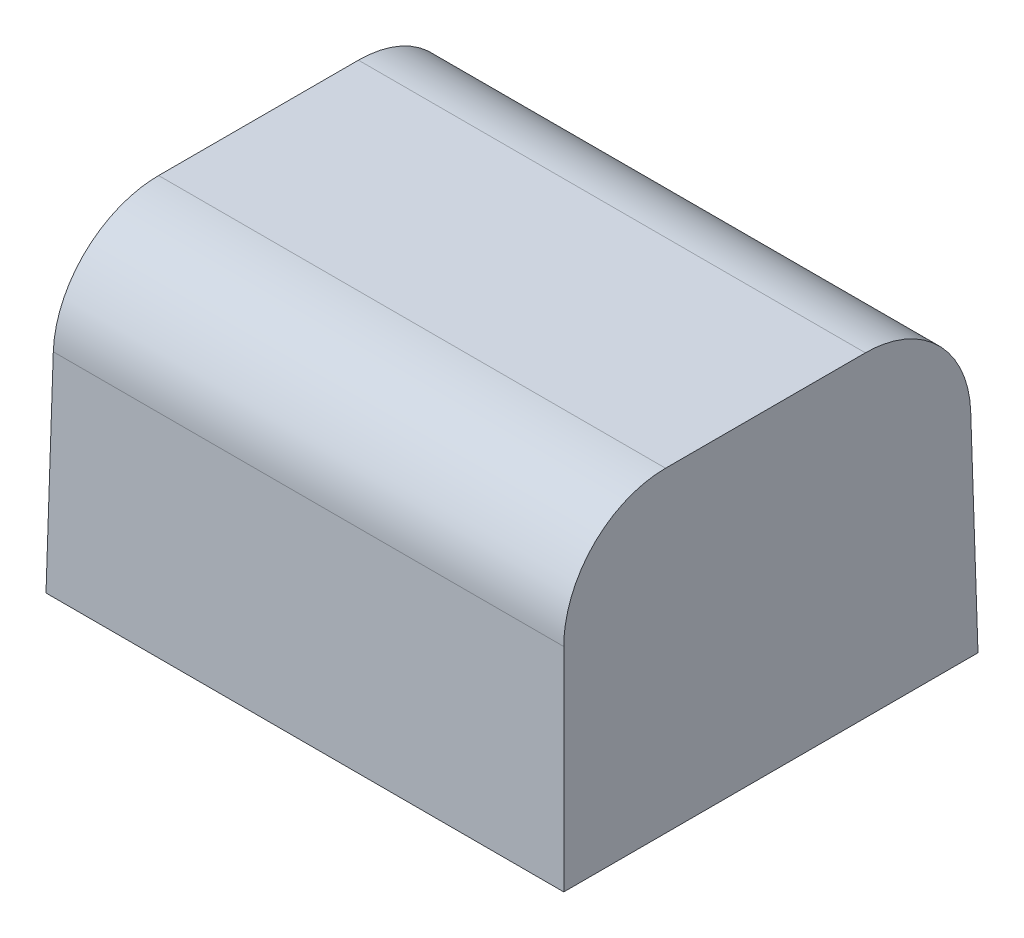
SolidWorks part; units mm, degrees
material "Liga 1060"
ref_plane "Plano frontal" through (0, 0, 0) normal (0, 0, 1) x (1, 0, 0)
ref_plane "Plano superior" through (0, 0, 0) normal (0, 1, 0) x (1, 0, 0)
ref_plane "Plano direito" through (0, 0, 0) normal (1, 0, 0) x (0, 0, -1)
sketch "Esboço1" plane through (0, 0, 0) normal (0, 1, 0) x (1, 0, 0)
  line L0 (0, 0) -> (50, 0)
  line L1 (50, 0) -> (50, 40)
  line L2 (50, 40) -> (0, 40)
  line L3 (0, 40) -> (0, 0)
  dimension "D1" = 50
  dimension "D2" = 40
extrude "Ressalto-extrusão1" add sketch "Esboço1" along normal blind 30 draft 1 contours L0 L1 L2 L3
fillet "Filete2" radius 10 2 edges at (25, 30, -39.4763) (25, 30, -0.5237)
